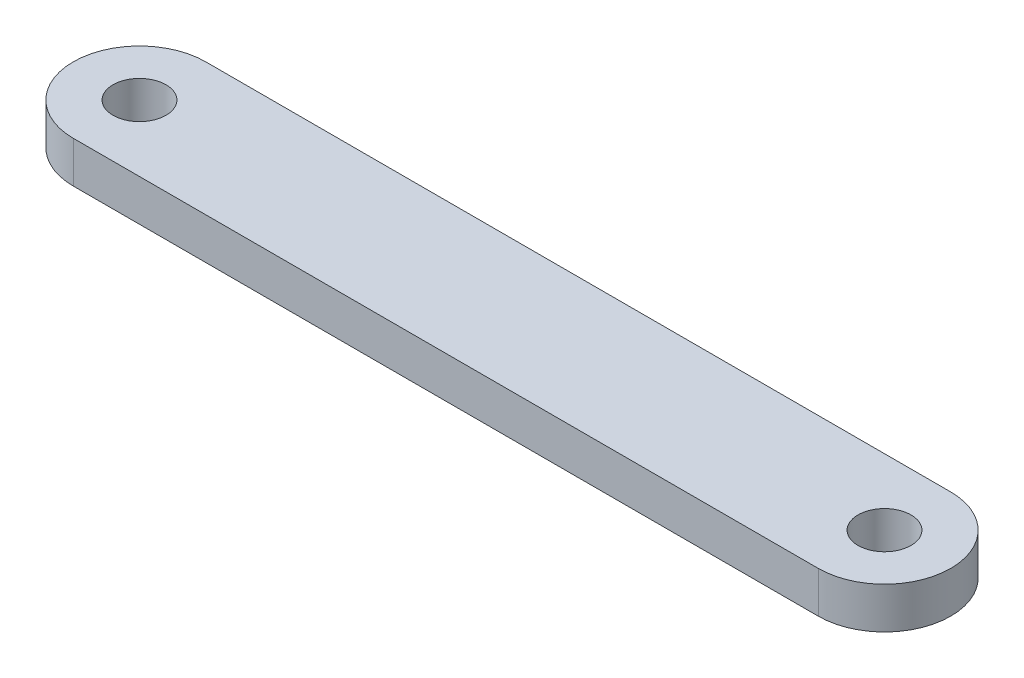
SolidWorks part; units mm, degrees
ref_plane "Front Plane" through (0, 0, 0) normal (0, 0, 1) x (1, 0, 0)
ref_plane "Top Plane" through (0, 0, 0) normal (0, 1, 0) x (1, 0, 0)
ref_plane "Right Plane" through (0, 0, 0) normal (1, 0, 0) x (0, 0, -1)
sketch "Sketch1" plane through (0, 0, 0) normal (0, 1, 0) x (1, 0, 0)
  line L0 (0, 0) -> (-57.15, 0) construction
  line L1 (0, -5.08) -> (-57.15, -5.08)
  line L2 (0, 5.08) -> (-57.15, 5.08)
  arc A0 (0, -5.08) -> (0, 5.08) centre (0, 0) ccw
  arc A1 (-57.15, 5.08) -> (-57.15, -5.08) centre (-57.15, 0) ccw
  circle A2 centre (-57.15, 0) radius 2.032
  circle A3 centre (0, 0) radius 2.032
  point P3 (-28.575, 0)
  dimension "D2" = 5.08
  dimension "D3" = 4.064
  dimension "D1" = 57.15
extrude "Boss-Extrude1" add sketch "Sketch1" along normal blind 3.175
